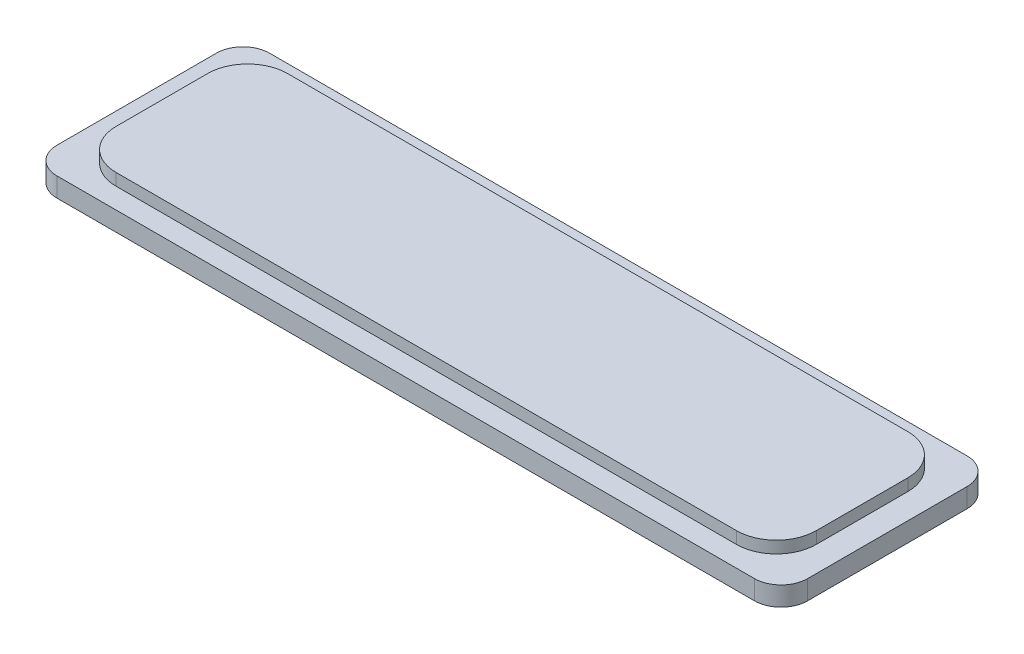
SolidWorks part; units mm, degrees
ref_plane "Front Plane" through (0, 0, 0) normal (0, 0, 1) x (1, 0, 0)
ref_plane "Top Plane" through (0, 0, 0) normal (0, 1, 0) x (1, 0, 0)
ref_plane "Right Plane" through (0, 0, 0) normal (1, 0, 0) x (0, 0, -1)
sketch "Sketch1" plane through (0, 0, 0) normal (0, 1, 0) x (1, 0, 0)
  line L1 (-26.25, -8) -> (26.25, -8)
  line L2 (-28.25, -6) -> (-28.25, 6)
  line L3 (-26.25, 8) -> (26.25, 8)
  line L4 (28.25, -6) -> (28.25, 6)
  line L5 (-28.25, -8) -> (28.25, 8) construction
  line L6 (-28.25, 8) -> (28.25, -8) construction
  arc A0 (26.25, 8) -> (28.25, 6) centre (26.25, 6) cw
  arc A1 (26.25, -8) -> (28.25, -6) centre (26.25, -6) ccw
  arc A2 (-26.25, -8) -> (-28.25, -6) centre (-26.25, -6) cw
  arc A3 (-28.25, 6) -> (-26.25, 8) centre (-26.25, 6) cw
  point P0 (0, 0)
  dimension "D3" = 2
  dimension "D1" = 56.5
  dimension "D2" = 16
extrude "Boss-Extrude1" add sketch "Sketch1" along normal blind 1.45
sketch "Sketch2" plane through (0, 1.45, 0) normal (0, 1, 0) x (1, 0, 0)
  line L1 (-23.35, -6.45) -> (23.35, -6.45)
  line L2 (-26.35, -3.45) -> (-26.35, 3.45)
  line L3 (-23.35, 6.45) -> (23.35, 6.45)
  line L4 (26.35, -3.45) -> (26.35, 3.45)
  line L5 (-26.35, -6.45) -> (26.35, 6.45) construction
  line L6 (-26.35, 6.45) -> (26.35, -6.45) construction
  arc A0 (23.35, -6.45) -> (26.35, -3.45) centre (23.35, -3.45) ccw
  arc A1 (23.35, 6.45) -> (26.35, 3.45) centre (23.35, 3.45) cw
  arc A2 (-23.35, -6.45) -> (-26.35, -3.45) centre (-23.35, -3.45) cw
  arc A3 (-26.35, 3.45) -> (-23.35, 6.45) centre (-23.35, 3.45) cw
  point P0 (0, 0)
  dimension "D3" = 3
  dimension "D1" = 52.7
  dimension "D2" = 12.9
extrude "Boss-Extrude2" add sketch "Sketch2" along normal blind 0.9
